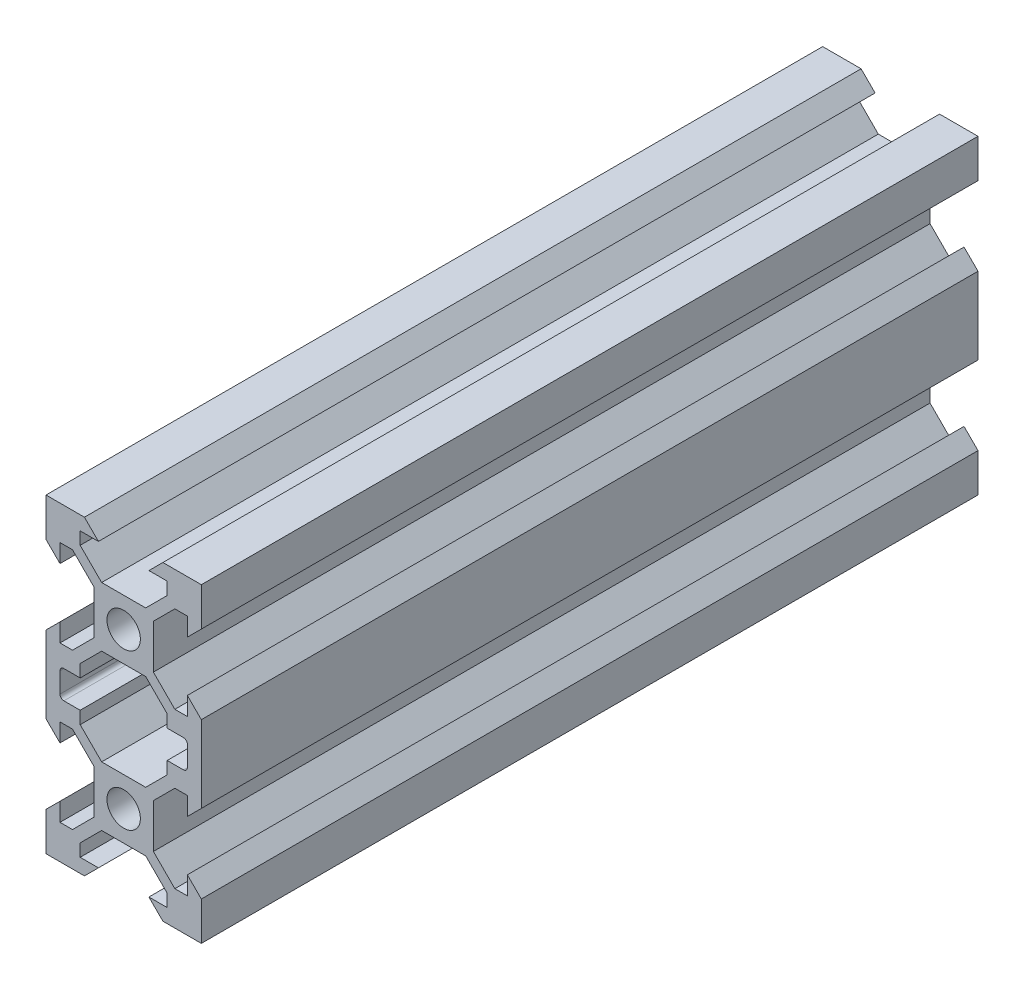
SolidWorks part; units mm, degrees
ref_plane "Alzado" through (0, 0, 0) normal (0, 0, 1) x (1, 0, 0)
ref_plane "Planta" through (0, 0, 0) normal (0, 1, 0) x (1, 0, 0)
ref_plane "Vista lateral" through (0, 0, 0) normal (1, 0, 0) x (0, 0, -1)
sketch "Croquis1" plane through (0, 0, 0) normal (0, 0, 1) x (1, 0, 0)
  line L0 (0, 0) -> (0, -20) construction
  line L2 (0, 0) -> (0, -0.5674)
  line L5 (6.175, -7.1649) -> (6.175, -12.8351)
  line L6 (7.1649, -13.825) -> (12.8351, -13.825)
  line L7 (13.825, -7.1649) -> (13.825, -12.8351)
  line L8 (7.1649, -6.175) -> (12.8351, -6.175)
  line L9 (6.175, -13.825) -> (13.825, -13.825) construction
  line L10 (13.825, -6.175) -> (13.825, -13.825) construction
  line L12 (10, -10) -> (32.1172, -10) construction
  line L13 (13.25, -18.2) -> (15.05, -20)
  line L14 (20, -20) -> (15.6, -20)
  line L15 (20, -20) -> (20, -15.6)
  line L16 (18.2, -15.6) -> (16.5899, -15.6)
  line L32 (15.6, -18.2) -> (15.6, -16.5899)
  line L33 (10, -10) -> (10, -23.2493) construction
  line L34 (4.4, -18.2) -> (4.4, -16.5899)
  line L35 (7.1649, -13.825) -> (4.4, -16.5899)
  line L36 (15.6, -18.2) -> (13.25, -18.2)
  line L38 (15.6, -20) -> (15.05, -20)
  line L40 (15.05, -20) -> (20, -20)
  line L41 (0, -20) -> (20, -20) construction
  line L42 (6.175, -12.8351) -> (3.4101, -15.6)
  line L43 (18.2, -13.25) -> (20, -15.05)
  line L44 (20, -20) -> (18.2, -20)
  line L45 (20, -20) -> (20, -15.05)
  line L48 (20, -15.05) -> (20, -20)
  line L49 (20, 0) -> (20, -20) construction
  line L50 (18.2, -15.6) -> (18.2, -13.25)
  line L51 (12.8351, -13.825) -> (15.6, -16.5899)
  line L52 (13.825, -12.8351) -> (16.5899, -15.6)
  line L53 (1.8, -15.6) -> (3.4101, -15.6)
  line L54 (1.8, -15.6) -> (1.8, -13.25)
  line L55 (1.8, -13.25) -> (0, -15.05)
  line L56 (0, 0) -> (20, 0) construction
  line L57 (0, -20) -> (0, -15.6)
  line L58 (0, -15.6) -> (0, -15.05)
  line L59 (0, -20) -> (4.4, -20)
  line L60 (0, -20) -> (4.95, -20)
  line L61 (6.75, -18.2) -> (4.95, -20)
  line L62 (4.4, -18.2) -> (6.75, -18.2)
  line L63 (1.8, -4.4) -> (3.4101, -4.4)
  line L64 (6.175, -7.1649) -> (3.4101, -4.4)
  line L65 (7.1649, -6.175) -> (4.4, -3.4101)
  line L66 (4.4, -1.8) -> (4.4, -3.4101)
  line L71 (0, 0) -> (0, -4.4)
  line L72 (0, 0) -> (0, -4.95)
  line L73 (1.8, -6.75) -> (0, -4.95)
  line L74 (1.8, -4.4) -> (1.8, -6.75)
  line L75 (15.6, -1.8) -> (15.6, -3.4101)
  line L76 (12.8351, -6.175) -> (15.6, -3.4101)
  line L77 (13.825, -7.1649) -> (16.5899, -4.4)
  line L78 (18.2, -4.4) -> (16.5899, -4.4)
  line L79 (18.2, -4.4) -> (18.2, -6.75)
  line L80 (18.2, -6.75) -> (20, -4.95)
  line L81 (20, 0) -> (20, -4.4)
  line L82 (20, -4.4) -> (20, -4.95)
  line L87 (6.175, -6.175) -> (13.825, -6.175) construction
  line L88 (6.175, -6.175) -> (6.175, -13.825) construction
  line L89 (0, 20) -> (0, 19.4326)
  line L90 (6.175, 12.8351) -> (6.175, 7.1649)
  line L91 (7.1649, 6.175) -> (12.8351, 6.175)
  line L92 (13.825, 12.8351) -> (13.825, 7.1649)
  line L93 (7.1649, 13.825) -> (12.8351, 13.825)
  line L96 (20, 0) -> (20, 4.4)
  line L97 (18.2, 4.4) -> (16.5899, 4.4)
  line L98 (15.6, 1.8) -> (15.6, 3.4101)
  line L99 (4.4, 1.8) -> (4.4, 3.4101)
  line L100 (7.1649, 6.175) -> (4.4, 3.4101)
  line L104 (6.175, 7.1649) -> (3.4101, 4.4)
  line L105 (18.2, 6.75) -> (20, 4.95)
  line L107 (20, 0) -> (20, 4.95)
  line L108 (20, 4.95) -> (20, 0)
  line L109 (18.2, 4.4) -> (18.2, 6.75)
  line L110 (12.8351, 6.175) -> (15.6, 3.4101)
  line L111 (13.825, 7.1649) -> (16.5899, 4.4)
  line L112 (1.8, 4.4) -> (3.4101, 4.4)
  line L113 (1.8, 4.4) -> (1.8, 6.75)
  line L114 (1.8, 6.75) -> (0, 4.95)
  line L115 (0, 0) -> (0, 4.4)
  line L116 (0, 4.4) -> (0, 4.95)
  line L121 (1.8, 15.6) -> (3.4101, 15.6)
  line L122 (6.175, 12.8351) -> (3.4101, 15.6)
  line L123 (7.1649, 13.825) -> (4.4, 16.5899)
  line L124 (4.4, 18.2) -> (4.4, 16.5899)
  line L125 (4.4, 18.2) -> (6.75, 18.2)
  line L126 (6.75, 18.2) -> (4.95, 20)
  line L127 (0, 20) -> (4.4, 20)
  line L128 (4.4, 20) -> (4.95, 20)
  line L129 (0, 20) -> (0, 15.6)
  line L130 (0, 20) -> (0, 15.05)
  line L131 (1.8, 13.25) -> (0, 15.05)
  line L132 (1.8, 15.6) -> (1.8, 13.25)
  line L133 (15.6, 18.2) -> (15.6, 16.5899)
  line L134 (12.8351, 13.825) -> (15.6, 16.5899)
  line L135 (13.825, 12.8351) -> (16.5899, 15.6)
  line L136 (18.2, 15.6) -> (16.5899, 15.6)
  line L137 (18.2, 15.6) -> (18.2, 13.25)
  line L138 (18.2, 13.25) -> (20, 15.05)
  line L139 (20, 20) -> (20, 15.6)
  line L140 (20, 15.6) -> (20, 15.05)
  line L141 (20, 20) -> (15.6, 20)
  line L142 (20, 20) -> (15.05, 20)
  line L143 (13.25, 18.2) -> (15.05, 20)
  line L144 (15.6, 18.2) -> (13.25, 18.2)
  line L146 (4.4, 1.8) -> (2.3, 1.8)
  line L147 (10, 10) -> (10, -3.2493) construction
  line L148 (10, 10) -> (32.1172, 10) construction
  line L150 (4.4, -1.8) -> (2.3, -1.8)
  line L151 (1.8, 1.3) -> (1.8, -1.3)
  line L152 (15.6, -1.8) -> (17.7, -1.8)
  line L154 (15.6, 1.8) -> (17.7, 1.8)
  line L155 (18.2, -1.3) -> (18.2, 1.3)
  line L156 (4.4, 1.8) -> (6.75, 1.8) [skipped]
  line L157 (6.75, 1.8) -> (4.95, 0) [skipped]
  line L158 (6.75, -1.8) -> (4.95, 0) [skipped]
  line L159 (4.4, -1.8) -> (6.75, -1.8) [skipped]
  line L160 (15.6, -1.8) -> (13.25, -1.8) [skipped]
  line L161 (13.25, -1.8) -> (15.05, 0) [skipped]
  line L162 (13.25, 1.8) -> (15.05, 0) [skipped]
  line L163 (15.6, 1.8) -> (13.25, 1.8) [skipped]
  line L164 (15.6, 0) -> (15.05, 0) [skipped]
  line L165 (4.4, 0) -> (4.95, 0) [skipped]
  line L166 (20, 0) -> (18.2, 0) [skipped]
  line L167 (18.2, 0) -> (20, 0) [skipped]
  line L168 (20, 0) -> (18.2, 0) [skipped]
  line L169 (20, 0) -> (18.2, 0) [skipped]
  line L170 (20, 0) -> (18.2, 0) [skipped]
  line L171 (0, 0) -> (1.8, 0) [skipped]
  line L172 (0, 0) -> (1.8, 0) [skipped]
  line L173 (0, 0) -> (1.8, 0) [skipped]
  circle A0 centre (10, -10) radius 2.15
  circle A1 centre (10, 10) radius 2.15
  arc A2 (17.7, 1.8) -> (18.2, 1.3) centre (17.7, 1.3) cw
  arc A3 (17.7, -1.8) -> (18.2, -1.3) centre (17.7, -1.3) ccw
  arc A4 (2.3, -1.8) -> (1.8, -1.3) centre (2.3, -1.3) cw
  arc A5 (2.3, 1.8) -> (1.8, 1.3) centre (2.3, 1.3) ccw
  point P69 (10, -10)
  point P128 (10, 10)
  dimension "D3" = 4.3
  dimension "D5" = 0.5
  dimension "D2" = 4
  dimension "D4" = 2
  dimension "D11" = 4.4
  dimension "D15" = 4.4
  dimension "D16" = 6.75
extrude "Saliente-Extruir1" add sketch "Croquis1" along normal blind 100 contours L144 L133 L134 L93 L123 L124 L125 L126 L128 L127 L89 L129 L130 L131 L132 L121 L122 L90 L104 L112 L113 L114 L116 L115 L2 L71 L72 L73 L74 L63 L64 L5 L42 L53 L54 L55 L58 L57 L59 L60 L61 L62 L34 L35 L6 L51 L32 L36 L13 L38 L40
